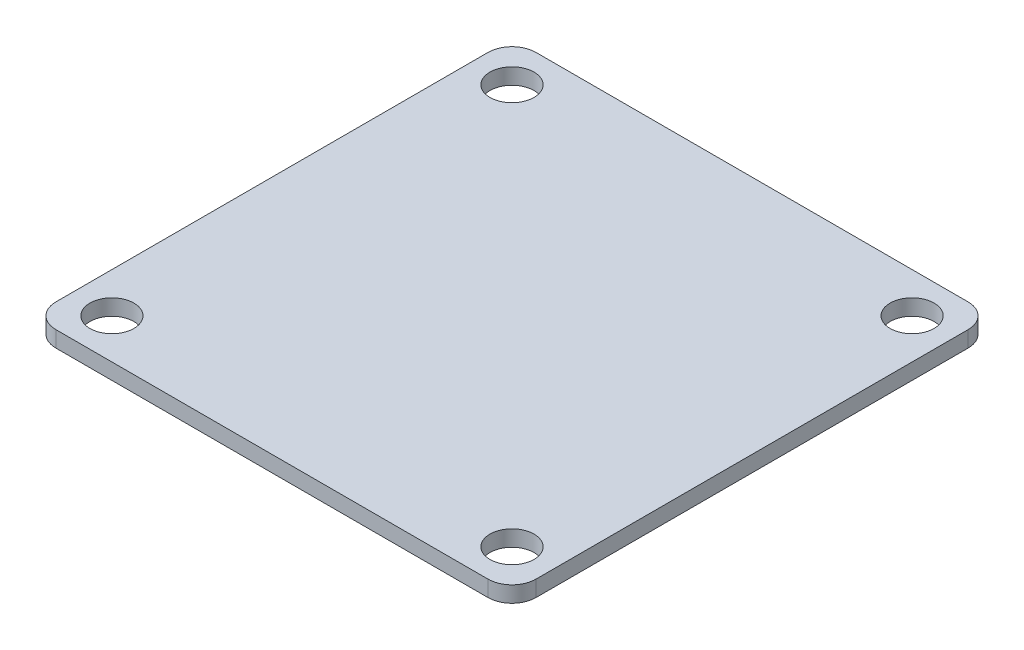
SolidWorks part; units mm, degrees
ref_plane "Front Plane" through (0, 0, 0) normal (0, 0, 1) x (1, 0, 0)
ref_plane "Top Plane" through (0, 0, 0) normal (0, 1, 0) x (1, 0, 0)
ref_plane "Right Plane" through (0, 0, 0) normal (1, 0, 0) x (0, 0, -1)
sketch "Sketch1" plane through (0, 0, 0) normal (0, 1, 0) x (1, 0, 0)
  line L0 (0, 3) -> (0, 57)
  line L1 (3, 60) -> (57, 60)
  line L2 (60, 57) -> (60, 3)
  line L3 (57, 0) -> (3, 0)
  circle A0 centre (5, 55) radius 2.75
  circle A1 centre (5, 5) radius 2.75
  circle A2 centre (55, 5) radius 2.75
  circle A3 centre (55, 55) radius 2.75
  arc A4 (60, 57) -> (57, 60) centre (57, 57) ccw
  arc A5 (57, 0) -> (60, 3) centre (57, 3) ccw
  arc A6 (3, 0) -> (0, 3) centre (3, 3) cw
  arc A7 (0, 57) -> (3, 60) centre (3, 57) cw
  point P9 (60, 60)
  point P20 (0, 0)
  point P23 (0, 60)
  dimension "D3" = 5.5
  dimension "D4" = 5
  dimension "D5" = 5
  dimension "D6" = 3
  dimension "D1" = 60
  dimension "D2" = 60
extrude "Boss-Extrude1" add sketch "Sketch1" along normal blind 2
